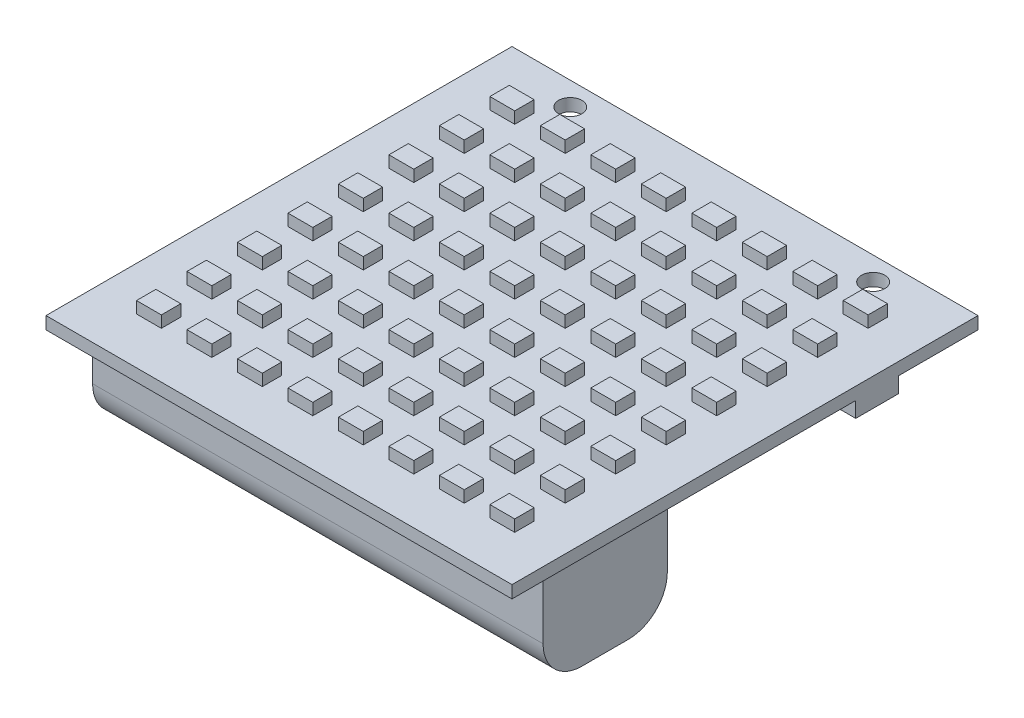
SolidWorks part; units mm, degrees
ref_plane "Front Plane" through (0, 0, 0) normal (0, 0, 1) x (1, 0, 0)
ref_plane "Top Plane" through (0, 0, 0) normal (0, 1, 0) x (1, 0, 0)
ref_plane "Right Plane" through (0, 0, 0) normal (1, 0, 0) x (0, 0, -1)
sketch "Sketch1" plane through (0, 0, 0) normal (0, 1, 0) x (1, 0, 0)
  line L1 (-35.5371, 27.7853) -> (24.4629, 27.7853)
  line L2 (-35.5371, 27.7853) -> (-35.5371, -32.2147)
  line L3 (-35.5371, -32.2147) -> (24.4629, -32.2147)
  line L4 (24.4629, 27.7853) -> (24.4629, -32.2147)
  dimension "D1" = 60
  dimension "D2" = 60
extrude "Boss-Extrude1" add sketch "Sketch1" along normal blind 1.6
sketch "Sketch2" plane through (0, 1.6, 0) normal (0, 1, 0) x (1, 0, 0)
  line L0 (-23.3871, 21.7853) -> (-20.1871, 21.7853)
  line L1 (-29.8871, 21.7853) -> (-26.6871, 21.7853)
  line L2 (-29.8871, 21.7853) -> (-29.8871, 19.2853)
  line L3 (-29.8871, 19.2853) -> (-26.6871, 19.2853)
  line L4 (-26.6871, 21.7853) -> (-26.6871, 19.2853)
  line L5 (-23.3871, 21.7853) -> (-23.3871, 19.2853)
  line L6 (-23.3871, 19.2853) -> (-20.1871, 19.2853)
  line L7 (-20.1871, 21.7853) -> (-20.1871, 19.2853)
  line L8 (-16.8871, 21.7853) -> (-13.6871, 21.7853)
  line L9 (-16.8871, 21.7853) -> (-16.8871, 19.2853)
  line L10 (-16.8871, 19.2853) -> (-13.6871, 19.2853)
  line L11 (-13.6871, 21.7853) -> (-13.6871, 19.2853)
  line L12 (-10.3871, 21.7853) -> (-7.1871, 21.7853)
  line L13 (-10.3871, 21.7853) -> (-10.3871, 19.2853)
  line L14 (-10.3871, 19.2853) -> (-7.1871, 19.2853)
  line L15 (-7.1871, 21.7853) -> (-7.1871, 19.2853)
  line L16 (-3.8871, 21.7853) -> (-0.6871, 21.7853)
  line L17 (-3.8871, 21.7853) -> (-3.8871, 19.2853)
  line L18 (-3.8871, 19.2853) -> (-0.6871, 19.2853)
  line L19 (-0.6871, 21.7853) -> (-0.6871, 19.2853)
  line L20 (2.6129, 21.7853) -> (5.8129, 21.7853)
  line L21 (2.6129, 21.7853) -> (2.6129, 19.2853)
  line L22 (2.6129, 19.2853) -> (5.8129, 19.2853)
  line L23 (5.8129, 21.7853) -> (5.8129, 19.2853)
  line L24 (9.1129, 21.7853) -> (12.3129, 21.7853)
  line L25 (9.1129, 21.7853) -> (9.1129, 19.2853)
  line L26 (9.1129, 19.2853) -> (12.3129, 19.2853)
  line L27 (12.3129, 21.7853) -> (12.3129, 19.2853)
  line L28 (15.6129, 21.7853) -> (18.8129, 21.7853)
  line L29 (15.6129, 21.7853) -> (15.6129, 19.2853)
  line L30 (15.6129, 19.2853) -> (18.8129, 19.2853)
  line L31 (18.8129, 21.7853) -> (18.8129, 19.2853)
  line L32 (-23.3871, 15.2853) -> (-20.1871, 15.2853)
  line L33 (-23.3871, 15.2853) -> (-23.3871, 12.7853)
  line L34 (-23.3871, 12.7853) -> (-20.1871, 12.7853)
  line L35 (-20.1871, 15.2853) -> (-20.1871, 12.7853)
  line L36 (-16.8871, 15.2853) -> (-13.6871, 15.2853)
  line L37 (-16.8871, 15.2853) -> (-16.8871, 12.7853)
  line L38 (-16.8871, 12.7853) -> (-13.6871, 12.7853)
  line L39 (-13.6871, 15.2853) -> (-13.6871, 12.7853)
  line L40 (-10.3871, 15.2853) -> (-7.1871, 15.2853)
  line L41 (-10.3871, 15.2853) -> (-10.3871, 12.7853)
  line L42 (-10.3871, 12.7853) -> (-7.1871, 12.7853)
  line L43 (-7.1871, 15.2853) -> (-7.1871, 12.7853)
  line L44 (-3.8871, 15.2853) -> (-0.6871, 15.2853)
  line L45 (-3.8871, 15.2853) -> (-3.8871, 12.7853)
  line L46 (-3.8871, 12.7853) -> (-0.6871, 12.7853)
  line L47 (-0.6871, 15.2853) -> (-0.6871, 12.7853)
  line L48 (2.6129, 15.2853) -> (5.8129, 15.2853)
  line L49 (2.6129, 15.2853) -> (2.6129, 12.7853)
  line L50 (2.6129, 12.7853) -> (5.8129, 12.7853)
  line L51 (5.8129, 15.2853) -> (5.8129, 12.7853)
  line L52 (9.1129, 15.2853) -> (12.3129, 15.2853)
  line L53 (9.1129, 15.2853) -> (9.1129, 12.7853)
  line L54 (9.1129, 12.7853) -> (12.3129, 12.7853)
  line L55 (12.3129, 15.2853) -> (12.3129, 12.7853)
  line L56 (15.6129, 15.2853) -> (18.8129, 15.2853)
  line L57 (15.6129, 15.2853) -> (15.6129, 12.7853)
  line L58 (15.6129, 12.7853) -> (18.8129, 12.7853)
  line L59 (18.8129, 15.2853) -> (18.8129, 12.7853)
  line L60 (-23.3871, 8.7853) -> (-20.1871, 8.7853)
  line L61 (-23.3871, 8.7853) -> (-23.3871, 6.2853)
  line L62 (-23.3871, 6.2853) -> (-20.1871, 6.2853)
  line L63 (-20.1871, 8.7853) -> (-20.1871, 6.2853)
  line L64 (-16.8871, 8.7853) -> (-13.6871, 8.7853)
  line L65 (-16.8871, 8.7853) -> (-16.8871, 6.2853)
  line L66 (-16.8871, 6.2853) -> (-13.6871, 6.2853)
  line L67 (-13.6871, 8.7853) -> (-13.6871, 6.2853)
  line L68 (-10.3871, 8.7853) -> (-7.1871, 8.7853)
  line L69 (-10.3871, 8.7853) -> (-10.3871, 6.2853)
  line L70 (-10.3871, 6.2853) -> (-7.1871, 6.2853)
  line L71 (-7.1871, 8.7853) -> (-7.1871, 6.2853)
  line L72 (-3.8871, 8.7853) -> (-0.6871, 8.7853)
  line L73 (-3.8871, 8.7853) -> (-3.8871, 6.2853)
  line L74 (-3.8871, 6.2853) -> (-0.6871, 6.2853)
  line L75 (-0.6871, 8.7853) -> (-0.6871, 6.2853)
  line L76 (2.6129, 8.7853) -> (5.8129, 8.7853)
  line L77 (2.6129, 8.7853) -> (2.6129, 6.2853)
  line L78 (2.6129, 6.2853) -> (5.8129, 6.2853)
  line L79 (5.8129, 8.7853) -> (5.8129, 6.2853)
  line L80 (9.1129, 8.7853) -> (12.3129, 8.7853)
  line L81 (9.1129, 8.7853) -> (9.1129, 6.2853)
  line L82 (9.1129, 6.2853) -> (12.3129, 6.2853)
  line L83 (12.3129, 8.7853) -> (12.3129, 6.2853)
  line L84 (15.6129, 8.7853) -> (18.8129, 8.7853)
  line L85 (15.6129, 8.7853) -> (15.6129, 6.2853)
  line L86 (15.6129, 6.2853) -> (18.8129, 6.2853)
  line L87 (18.8129, 8.7853) -> (18.8129, 6.2853)
  line L88 (-23.3871, 2.2853) -> (-20.1871, 2.2853)
  line L89 (-23.3871, 2.2853) -> (-23.3871, -0.2147)
  line L90 (-23.3871, -0.2147) -> (-20.1871, -0.2147)
  line L91 (-20.1871, 2.2853) -> (-20.1871, -0.2147)
  line L92 (-16.8871, 2.2853) -> (-13.6871, 2.2853)
  line L93 (-16.8871, 2.2853) -> (-16.8871, -0.2147)
  line L94 (-16.8871, -0.2147) -> (-13.6871, -0.2147)
  line L95 (-13.6871, 2.2853) -> (-13.6871, -0.2147)
  line L96 (-10.3871, 2.2853) -> (-7.1871, 2.2853)
  line L97 (-10.3871, 2.2853) -> (-10.3871, -0.2147)
  line L98 (-10.3871, -0.2147) -> (-7.1871, -0.2147)
  line L99 (-7.1871, 2.2853) -> (-7.1871, -0.2147)
  line L100 (-3.8871, 2.2853) -> (-0.6871, 2.2853)
  line L101 (-3.8871, 2.2853) -> (-3.8871, -0.2147)
  line L102 (-3.8871, -0.2147) -> (-0.6871, -0.2147)
  line L103 (-0.6871, 2.2853) -> (-0.6871, -0.2147)
  line L104 (2.6129, 2.2853) -> (5.8129, 2.2853)
  line L105 (2.6129, 2.2853) -> (2.6129, -0.2147)
  line L106 (2.6129, -0.2147) -> (5.8129, -0.2147)
  line L107 (5.8129, 2.2853) -> (5.8129, -0.2147)
  line L108 (9.1129, 2.2853) -> (12.3129, 2.2853)
  line L109 (9.1129, 2.2853) -> (9.1129, -0.2147)
  line L110 (9.1129, -0.2147) -> (12.3129, -0.2147)
  line L111 (12.3129, 2.2853) -> (12.3129, -0.2147)
  line L112 (15.6129, 2.2853) -> (18.8129, 2.2853)
  line L113 (15.6129, 2.2853) -> (15.6129, -0.2147)
  line L114 (15.6129, -0.2147) -> (18.8129, -0.2147)
  line L115 (18.8129, 2.2853) -> (18.8129, -0.2147)
  line L116 (-23.3871, -4.2147) -> (-20.1871, -4.2147)
  line L117 (-23.3871, -4.2147) -> (-23.3871, -6.7147)
  line L118 (-23.3871, -6.7147) -> (-20.1871, -6.7147)
  line L119 (-20.1871, -4.2147) -> (-20.1871, -6.7147)
  line L120 (-16.8871, -4.2147) -> (-13.6871, -4.2147)
  line L121 (-16.8871, -4.2147) -> (-16.8871, -6.7147)
  line L122 (-16.8871, -6.7147) -> (-13.6871, -6.7147)
  line L123 (-13.6871, -4.2147) -> (-13.6871, -6.7147)
  line L124 (-10.3871, -4.2147) -> (-7.1871, -4.2147)
  line L125 (-10.3871, -4.2147) -> (-10.3871, -6.7147)
  line L126 (-10.3871, -6.7147) -> (-7.1871, -6.7147)
  line L127 (-7.1871, -4.2147) -> (-7.1871, -6.7147)
  line L128 (-3.8871, -4.2147) -> (-0.6871, -4.2147)
  line L129 (-3.8871, -4.2147) -> (-3.8871, -6.7147)
  line L130 (-3.8871, -6.7147) -> (-0.6871, -6.7147)
  line L131 (-0.6871, -4.2147) -> (-0.6871, -6.7147)
  line L132 (2.6129, -4.2147) -> (5.8129, -4.2147)
  line L133 (2.6129, -4.2147) -> (2.6129, -6.7147)
  line L134 (2.6129, -6.7147) -> (5.8129, -6.7147)
  line L135 (5.8129, -4.2147) -> (5.8129, -6.7147)
  line L136 (9.1129, -4.2147) -> (12.3129, -4.2147)
  line L137 (9.1129, -4.2147) -> (9.1129, -6.7147)
  line L138 (9.1129, -6.7147) -> (12.3129, -6.7147)
  line L139 (12.3129, -4.2147) -> (12.3129, -6.7147)
  line L140 (15.6129, -4.2147) -> (18.8129, -4.2147)
  line L141 (15.6129, -4.2147) -> (15.6129, -6.7147)
  line L142 (15.6129, -6.7147) -> (18.8129, -6.7147)
  line L143 (18.8129, -4.2147) -> (18.8129, -6.7147)
  line L144 (-23.3871, -10.7147) -> (-20.1871, -10.7147)
  line L145 (-23.3871, -10.7147) -> (-23.3871, -13.2147)
  line L146 (-23.3871, -13.2147) -> (-20.1871, -13.2147)
  line L147 (-20.1871, -10.7147) -> (-20.1871, -13.2147)
  line L148 (-16.8871, -10.7147) -> (-13.6871, -10.7147)
  line L149 (-16.8871, -10.7147) -> (-16.8871, -13.2147)
  line L150 (-16.8871, -13.2147) -> (-13.6871, -13.2147)
  line L151 (-13.6871, -10.7147) -> (-13.6871, -13.2147)
  line L152 (-10.3871, -10.7147) -> (-7.1871, -10.7147)
  line L153 (-10.3871, -10.7147) -> (-10.3871, -13.2147)
  line L154 (-10.3871, -13.2147) -> (-7.1871, -13.2147)
  line L155 (-7.1871, -10.7147) -> (-7.1871, -13.2147)
  line L156 (-3.8871, -10.7147) -> (-0.6871, -10.7147)
  line L157 (-3.8871, -10.7147) -> (-3.8871, -13.2147)
  line L158 (-3.8871, -13.2147) -> (-0.6871, -13.2147)
  line L159 (-0.6871, -10.7147) -> (-0.6871, -13.2147)
  line L160 (2.6129, -10.7147) -> (5.8129, -10.7147)
  line L161 (2.6129, -10.7147) -> (2.6129, -13.2147)
  line L162 (2.6129, -13.2147) -> (5.8129, -13.2147)
  line L163 (5.8129, -10.7147) -> (5.8129, -13.2147)
  line L164 (9.1129, -10.7147) -> (12.3129, -10.7147)
  line L165 (9.1129, -10.7147) -> (9.1129, -13.2147)
  line L166 (9.1129, -13.2147) -> (12.3129, -13.2147)
  line L167 (12.3129, -10.7147) -> (12.3129, -13.2147)
  line L168 (15.6129, -10.7147) -> (18.8129, -10.7147)
  line L169 (15.6129, -10.7147) -> (15.6129, -13.2147)
  line L170 (15.6129, -13.2147) -> (18.8129, -13.2147)
  line L171 (18.8129, -10.7147) -> (18.8129, -13.2147)
  line L172 (-23.3871, -17.2147) -> (-20.1871, -17.2147)
  line L173 (-23.3871, -17.2147) -> (-23.3871, -19.7147)
  line L174 (-23.3871, -19.7147) -> (-20.1871, -19.7147)
  line L175 (-20.1871, -17.2147) -> (-20.1871, -19.7147)
  line L176 (-16.8871, -17.2147) -> (-13.6871, -17.2147)
  line L177 (-16.8871, -17.2147) -> (-16.8871, -19.7147)
  line L178 (-16.8871, -19.7147) -> (-13.6871, -19.7147)
  line L179 (-13.6871, -17.2147) -> (-13.6871, -19.7147)
  line L180 (-10.3871, -17.2147) -> (-7.1871, -17.2147)
  line L181 (-10.3871, -17.2147) -> (-10.3871, -19.7147)
  line L182 (-10.3871, -19.7147) -> (-7.1871, -19.7147)
  line L183 (-7.1871, -17.2147) -> (-7.1871, -19.7147)
  line L184 (-3.8871, -17.2147) -> (-0.6871, -17.2147)
  line L185 (-3.8871, -17.2147) -> (-3.8871, -19.7147)
  line L186 (-3.8871, -19.7147) -> (-0.6871, -19.7147)
  line L187 (-0.6871, -17.2147) -> (-0.6871, -19.7147)
  line L188 (2.6129, -17.2147) -> (5.8129, -17.2147)
  line L189 (2.6129, -17.2147) -> (2.6129, -19.7147)
  line L190 (2.6129, -19.7147) -> (5.8129, -19.7147)
  line L191 (5.8129, -17.2147) -> (5.8129, -19.7147)
  line L192 (9.1129, -17.2147) -> (12.3129, -17.2147)
  line L193 (9.1129, -17.2147) -> (9.1129, -19.7147)
  line L194 (9.1129, -19.7147) -> (12.3129, -19.7147)
  line L195 (12.3129, -17.2147) -> (12.3129, -19.7147)
  line L196 (15.6129, -17.2147) -> (18.8129, -17.2147)
  line L197 (15.6129, -17.2147) -> (15.6129, -19.7147)
  line L198 (15.6129, -19.7147) -> (18.8129, -19.7147)
  line L199 (18.8129, -17.2147) -> (18.8129, -19.7147)
  line L200 (-23.3871, -23.7147) -> (-20.1871, -23.7147)
  line L201 (-23.3871, -23.7147) -> (-23.3871, -26.2147)
  line L202 (-23.3871, -26.2147) -> (-20.1871, -26.2147)
  line L203 (-20.1871, -23.7147) -> (-20.1871, -26.2147)
  line L204 (-16.8871, -23.7147) -> (-13.6871, -23.7147)
  line L205 (-16.8871, -23.7147) -> (-16.8871, -26.2147)
  line L206 (-16.8871, -26.2147) -> (-13.6871, -26.2147)
  line L207 (-13.6871, -23.7147) -> (-13.6871, -26.2147)
  line L208 (-10.3871, -23.7147) -> (-7.1871, -23.7147)
  line L209 (-10.3871, -23.7147) -> (-10.3871, -26.2147)
  line L210 (-10.3871, -26.2147) -> (-7.1871, -26.2147)
  line L211 (-7.1871, -23.7147) -> (-7.1871, -26.2147)
  line L212 (-3.8871, -23.7147) -> (-0.6871, -23.7147)
  line L213 (-3.8871, -23.7147) -> (-3.8871, -26.2147)
  line L214 (-3.8871, -26.2147) -> (-0.6871, -26.2147)
  line L215 (-0.6871, -23.7147) -> (-0.6871, -26.2147)
  line L216 (2.6129, -23.7147) -> (5.8129, -23.7147)
  line L217 (2.6129, -23.7147) -> (2.6129, -26.2147)
  line L218 (2.6129, -26.2147) -> (5.8129, -26.2147)
  line L219 (5.8129, -23.7147) -> (5.8129, -26.2147)
  line L220 (9.1129, -23.7147) -> (12.3129, -23.7147)
  line L221 (9.1129, -23.7147) -> (9.1129, -26.2147)
  line L222 (9.1129, -26.2147) -> (12.3129, -26.2147)
  line L223 (12.3129, -23.7147) -> (12.3129, -26.2147)
  line L224 (15.6129, -23.7147) -> (18.8129, -23.7147)
  line L225 (15.6129, -23.7147) -> (15.6129, -26.2147)
  line L226 (15.6129, -26.2147) -> (18.8129, -26.2147)
  line L227 (18.8129, -23.7147) -> (18.8129, -26.2147)
  line L228 (-29.8871, 15.2853) -> (-26.6871, 15.2853)
  line L229 (-29.8871, 15.2853) -> (-29.8871, 12.7853)
  line L230 (-29.8871, 12.7853) -> (-26.6871, 12.7853)
  line L231 (-26.6871, 15.2853) -> (-26.6871, 12.7853)
  line L232 (-29.8871, 8.7853) -> (-26.6871, 8.7853)
  line L233 (-29.8871, 8.7853) -> (-29.8871, 6.2853)
  line L234 (-29.8871, 6.2853) -> (-26.6871, 6.2853)
  line L235 (-26.6871, 8.7853) -> (-26.6871, 6.2853)
  line L236 (-29.8871, 2.2853) -> (-26.6871, 2.2853)
  line L237 (-29.8871, 2.2853) -> (-29.8871, -0.2147)
  line L238 (-29.8871, -0.2147) -> (-26.6871, -0.2147)
  line L239 (-26.6871, 2.2853) -> (-26.6871, -0.2147)
  line L240 (-29.8871, -4.2147) -> (-26.6871, -4.2147)
  line L241 (-29.8871, -4.2147) -> (-29.8871, -6.7147)
  line L242 (-29.8871, -6.7147) -> (-26.6871, -6.7147)
  line L243 (-26.6871, -4.2147) -> (-26.6871, -6.7147)
  line L244 (-29.8871, -10.7147) -> (-26.6871, -10.7147)
  line L245 (-29.8871, -10.7147) -> (-29.8871, -13.2147)
  line L246 (-29.8871, -13.2147) -> (-26.6871, -13.2147)
  line L247 (-26.6871, -10.7147) -> (-26.6871, -13.2147)
  line L248 (-29.8871, -17.2147) -> (-26.6871, -17.2147)
  line L249 (-29.8871, -17.2147) -> (-29.8871, -19.7147)
  line L250 (-29.8871, -19.7147) -> (-26.6871, -19.7147)
  line L251 (-26.6871, -17.2147) -> (-26.6871, -19.7147)
  line L252 (-29.8871, -23.7147) -> (-26.6871, -23.7147)
  line L253 (-29.8871, -23.7147) -> (-29.8871, -26.2147)
  line L254 (-29.8871, -26.2147) -> (-26.6871, -26.2147)
  line L255 (-26.6871, -23.7147) -> (-26.6871, -26.2147)
  line L256 (-26.6871, 19.2853) -> (-29.8871, 21.7853) construction
  line L257 (-35.5371, 27.7853) -> (-35.5371, -32.2147) construction
  line L258 (24.4629, 27.7853) -> (-35.5371, 27.7853) construction
  point P4 (-28.2871, 20.5353)
  dimension "D1" = 3.2
  dimension "D2" = 2.5
  dimension "D5" = 6.5
  dimension "D6" = 6.5
  dimension "D7" = 7.25
  dimension "D8" = 7.25
  dimension "D3" = 8
  dimension "D4" = 8
extrude "Boss-Extrude2" add sketch "Sketch2" along normal blind 1.5
sketch "Sketch4" plane through (0, 0, 0) normal (0, -1, 0) x (1, 0, 0)
  line L0 (-5.5371, 11.2147) -> (-5.5371, 27.2147) construction
  line L1 (23.4629, 11.2147) -> (-34.5371, 11.2147)
  line L2 (23.4629, 11.2147) -> (23.4629, 27.2147)
  line L3 (23.4629, 27.2147) -> (-34.5371, 27.2147)
  line L4 (-34.5371, 11.2147) -> (-34.5371, 27.2147)
  line L5 (23.4629, 19.2147) -> (-5.5371, 19.2147) construction
  line L6 (-35.5371, 32.2147) -> (24.4629, 32.2147) construction
  point P8 (-5.5371, 32.2147)
  dimension "D1" = 58
  dimension "D2" = 16
  dimension "D3" = 5
extrude "Boss-Extrude3" add sketch "Sketch4" along normal blind 13
fillet "Fillet1" radius 5 2 edges at (-5.5371, -13, 11.2147) (-5.5371, -13, 27.2147)
sketch "Sketch5" plane through (0, 1.6, 0) normal (0, 1, 0) x (1, 0, 0)
  line L0 (24.4629, 27.7853) -> (-35.5371, 27.7853) construction
  line L1 (-5.5371, 27.7853) -> (-5.5371, -32.2147) construction
  line L2 (-35.5371, -32.2147) -> (24.4629, -32.2147) construction
  circle A0 centre (-25.0371, 24.7853) radius 1.5
  circle A1 centre (13.9629, 24.7853) radius 1.5
  dimension "D1" = 3
  dimension "D3" = 3
  dimension "D2" = 19.5
extrude "Cut-Extrude1" cut sketch "Sketch5" against normal up to next
sketch "Sketch6" plane through (0, 0, 0) normal (0, -1, 0) x (1, 0, 0)
  line L1 (-12.8842, -21.2092) -> (-32.8842, -21.2092)
  line L2 (-12.8842, -21.2092) -> (-12.8842, -4.2092)
  line L3 (-12.8842, -4.2092) -> (-32.8842, -4.2092)
  line L4 (-32.8842, -21.2092) -> (-32.8842, -4.2092)
  dimension "D1" = 20
  dimension "D2" = 17
extrude "Boss-Extrude4" add sketch "Sketch6" along normal blind 3.2
sketch "Sketch7" plane through (0, 0, 0) normal (0, -1, 0) x (1, 0, 0)
  line L0 (24.4629, 32.2147) -> (24.4629, -27.7853) construction
  line L1 (24.4629, -17.5443) -> (20.4629, -17.5443)
  line L2 (24.4629, -17.5443) -> (24.4629, -12.0443)
  line L3 (24.4629, -12.0443) -> (20.4629, -12.0443)
  line L4 (20.4629, -17.5443) -> (20.4629, -12.0443)
  dimension "D1" = 5.5
  dimension "D2" = 4
extrude "Boss-Extrude5" add sketch "Sketch7" along normal blind 2
